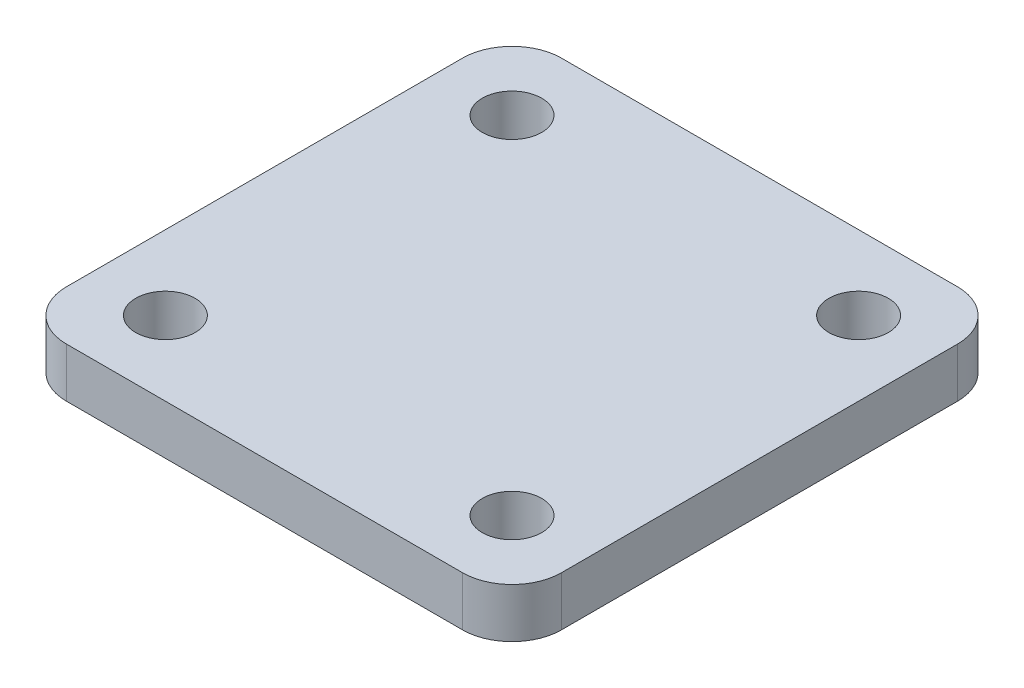
SolidWorks part; units mm, degrees
material "FE360"
ref_plane "Piano frontale" through (0, 0, 0) normal (0, 0, 1) x (1, 0, 0)
ref_plane "Piano superiore" through (0, 0, 0) normal (0, 1, 0) x (1, 0, 0)
ref_plane "Piano destro" through (0, 0, 0) normal (1, 0, 0) x (0, 0, -1)
sketch "Schizzo1" plane through (0, 0, 0) normal (0, 1, 0) x (1, 0, 0)
  line L1 (50, -50) -> (-50, -50)
  line L2 (50, -50) -> (50, 50)
  line L3 (50, 50) -> (-50, 50)
  line L4 (-50, -50) -> (-50, 50)
  line L5 (50, -50) -> (-50, 50) construction
  line L6 (50, 50) -> (-50, -50) construction
  circle A0 centre (-35, 35) radius 6
  circle A1 centre (35, 35) radius 6
  circle A2 centre (-35, -35) radius 6
  circle A3 centre (35, -35) radius 6
  point P0 (0, 0)
  dimension "D3" = 12
  dimension "D4" = 70
  dimension "D1" = 100
  dimension "D2" = 100
extrude "Estrusione-Estrusione1" add sketch "Schizzo1" along normal blind 10
fillet "Raccordo1" radius 10 4 edges at (-50, 5, 50) (-50, 5, -50) (50, 5, -50) (50, 5, 50)
